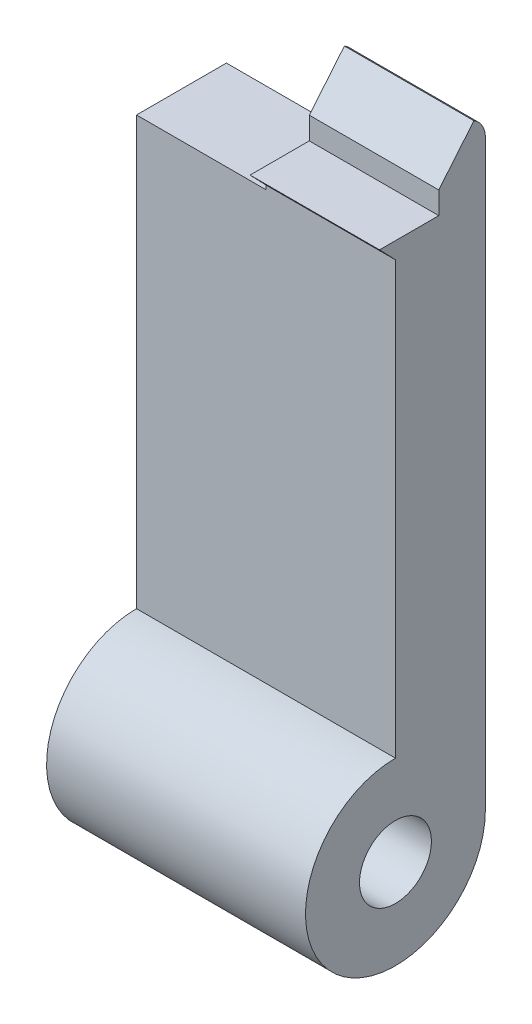
SolidWorks part; units mm, degrees
material "Plain Carbon Steel"
ref_plane "Front Plane" through (0, 0, 0) normal (0, 0, 1) x (1, 0, 0)
ref_plane "Top Plane" through (0, 0, 0) normal (0, 1, 0) x (1, 0, 0)
ref_plane "Right Plane" through (0, 0, 0) normal (1, 0, 0) x (0, 0, -1)
sketch "Sketch2" plane through (0, 0, 0) normal (1, 0, 0) x (0, 0, -1)
  line L0 (3.175, 0) -> (3.175, 20.574)
  line L1 (0, 3.175) -> (0, 18.415)
  line L2 (1.5299, 19.001) -> (1.5299, 20.574)
  line L3 (1.5299, 18.415) -> (-0.5614, 18.415)
  line L4 (1.5299, 18.415) -> (1.5299, 19.001)
  line L5 (1.5299, 19.001) -> (-0.5614, 19.001)
  line L6 (-0.5614, 18.415) -> (-0.5614, 19.001)
  line L7 (0, 18.415) -> (-0.5614, 19.001)
  line L8 (2.7705, 21.2824) -> (1.5299, 19.7875)
  circle A0 centre (0, 0) radius 1.27
  circle A1 centre (0, 0) radius 3.175
  arc A2 (1.5299, 20.574) -> (3.175, 20.574) centre (2.3524, 20.574) cw
  dimension "D1" = 2.54
  dimension "D2" = 6.35
  dimension "D3" = 15.24
  dimension "D4" = 20.574
extrude "Boss-Extrude1" add sketch "Sketch2" along normal blind 9.144 contours A2 L2 L4 L3 L1 A1 L0 | A1 A0 | L7 L3 L4 L5
sketch "Sketch3" plane through (0, 0, -3.175) normal (0, 0, -1) x (-1, 0, 0)
  line L0 (-9.144, 21.2824) -> (0, 21.2824) construction
  line L1 (-4.572, 21.2824) -> (0, 21.2824)
  line L2 (-4.572, 21.2824) -> (-4.572, 18.273)
  line L3 (-4.572, 18.273) -> (0, 18.273)
  line L4 (0, 21.2824) -> (0, 18.273)
  line L5 (0, 0) -> (0, 20.574) construction
extrude "Cut-Extrude1" cut sketch "Sketch3" against normal through all
